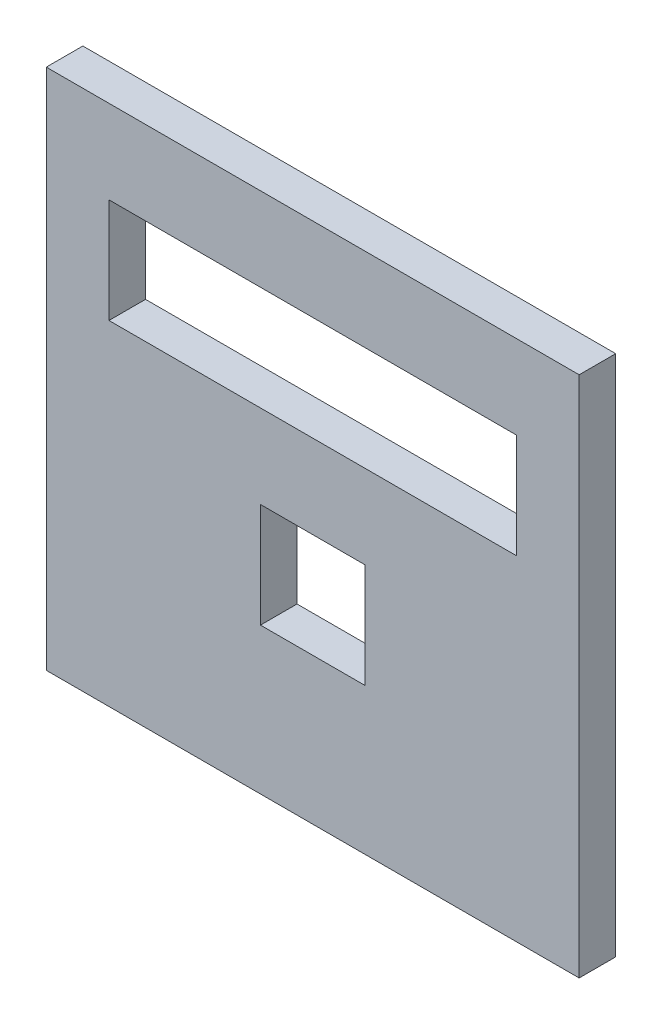
SolidWorks part; units mm, degrees
ref_plane "Front Plane" through (0, 0, 0) normal (0, 0, 1) x (1, 0, 0)
ref_plane "Top Plane" through (0, 0, 0) normal (0, 1, 0) x (1, 0, 0)
ref_plane "Right Plane" through (0, 0, 0) normal (1, 0, 0) x (0, 0, -1)
sketch "Sketch1" plane through (0, 0, 0) normal (0, 0, 1) x (1, 0, 0)
  line L0 (-12.75, 15) -> (-9.75, 15)
  line L1 (-12.75, -10) -> (12.75, -10)
  line L2 (-12.75, -10) -> (-12.75, 10)
  line L4 (12.75, -10) -> (12.75, 10)
  line L5 (-12.75, -10) -> (12.75, 10) construction
  line L6 (-12.75, 10) -> (12.75, -10) construction
  line L7 (-2.5, -3) -> (2.5, -3)
  line L8 (-2.5, -3) -> (-2.5, 2)
  line L9 (-2.5, 2) -> (2.5, 2)
  line L10 (2.5, -3) -> (2.5, 2)
  line L11 (-2.5, -3) -> (2.5, 2) construction
  line L12 (-2.5, 2) -> (2.5, -3) construction
  line L18 (-12.75, 10) -> (-12.75, 15)
  line L20 (12.75, 10) -> (12.75, 15)
  line L23 (-9.75, 6) -> (9.75, 6)
  line L25 (0, 15) -> (0, 11) construction
  line L26 (0, 6) -> (0, 2) construction
  line L27 (12.75, 15) -> (9.75, 15)
  line L28 (-9.75, 11) -> (9.75, 11)
  line L29 (-9.75, 15) -> (9.75, 15)
  line L30 (-9.75, 11) -> (-9.75, 6)
  line L31 (9.75, 11) -> (9.75, 6)
  point P0 (0, 0)
  point P6 (0, 0)
  point P13 (0, 15)
  dimension "D1" = 25.5
  dimension "D2" = 20
  dimension "D3" = 5
  dimension "D4" = 5
  dimension "D5" = 5
  dimension "D6" = 19.5
  dimension "D7" = 5
  dimension "D8" = 4
  dimension "D9" = 4
extrude "Boss-Extrude1" add sketch "Sketch1" along normal blind 1.75
